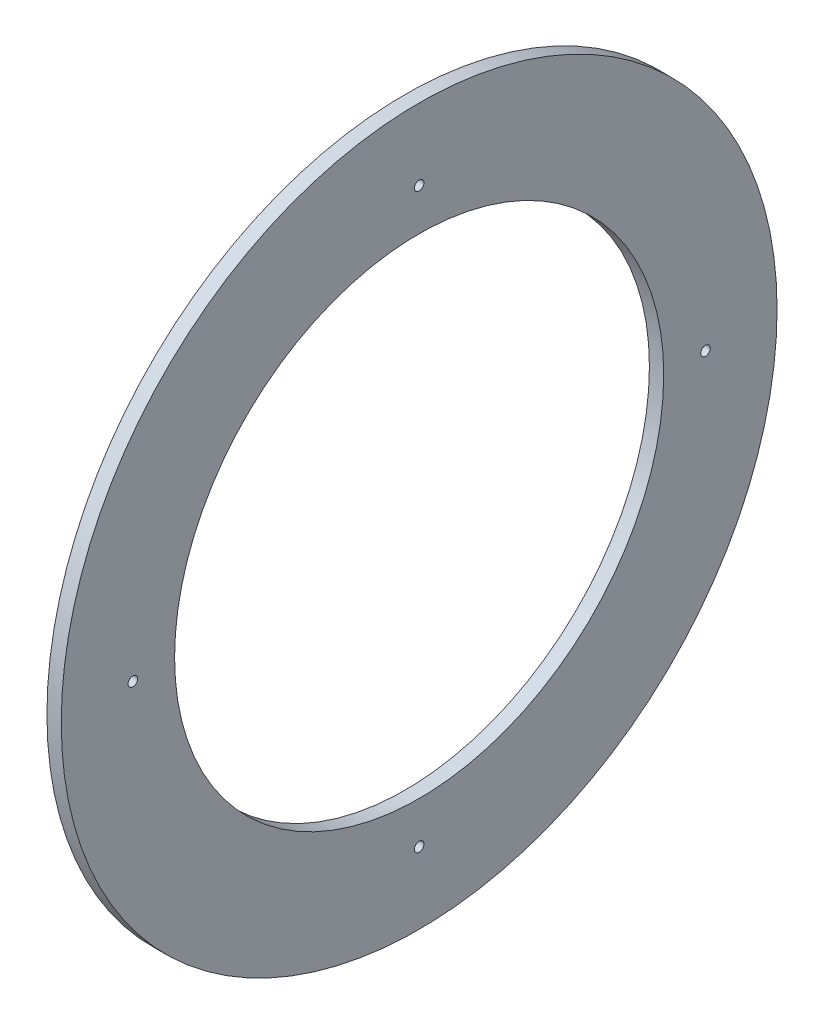
SolidWorks part; units mm, degrees
material "Balsa"
ref_plane "Plan de face" through (0, 0, 0) normal (0, 0, 1) x (1, 0, 0)
ref_plane "Plan de dessus" through (0, 0, 0) normal (0, 1, 0) x (1, 0, 0)
ref_plane "Plan de droite" through (0, 0, 0) normal (1, 0, 0) x (0, 0, -1)
sketch "Esquisse1" plane through (0, 0, 0) normal (1, 0, 0) x (0, 0, -1)
  circle A0 centre (0, 0) radius 51.25
  circle A1 centre (0, 0) radius 75
  dimension "D1" = 102.5
  dimension "D2" = 150
extrude "Boss.-Extru.1" add sketch "Esquisse1" along normal blind 3
sketch "Sketch1" plane through (3, 0, 0) normal (1, 0, 0) x (0, 0, -1)
  circle A0 centre (0, 60) radius 1
  circle A1 centre (60, 0) radius 1
  circle A2 centre (0, -60) radius 1
  circle A3 centre (-60, 0) radius 1
  point P11 (0, 0)
  dimension "D2" = 2
  dimension "D3" = 60
  dimension "D1" = 4
extrude "air vents" cut sketch "Sketch1" against normal through all
sketch "Sketch2" plane through (3, 0, 0) normal (1, 0, 0) x (0, 0, -1)
  line L0 (0, 0) -> (-48.0833, 48.0833) construction
  line L1 (-43.4871, 52.6795) -> (-81.6004, 90.7927)
  line L2 (-52.6795, 43.4871) -> (-92.274, 83.0816)
  line L3 (-92.274, 83.0816) -> (-81.6004, 90.7927)
  line L4 (0, 0) -> (0, 42.3711) construction
  arc A0 (-52.6795, 43.4871) -> (-43.4871, 52.6795) centre (-48.0833, 48.0833) ccw
  dimension "D1" = 13
  dimension "D2" = 68
  dimension "D3" = 45
extrude "Cut-Extrude1" [suppressed] cut sketch "Sketch2" against normal blind 10
equation "\"d_i_tube\"= 150mm'Inner Rocket Body Composite Tube Diameter"
equation "\"t_tube\"= 1.182mm'Thickness of Rocket Body Composite Tube"
equation "\"l_upper_body_tube\"= 949.3mm'Upper Rocket Body Composite Tube length"
equation "\"l_lower_body_tube\"= 816mm'Lower Rocket Body Composite Tube Length"
equation "\"d_a_NC\"= 154mm'Outer Diameter of Nosecone base"
equation "\"d_i_phenolic_tube\"= 152.3mm'Inner Phenolic Tube Diameter"
equation "\"t_phenolic_tube\"= 2mm'Thickness of Phenolic Body Tube"
equation "\"l_fin_cut\"= 220mm'Length of fin on Motor Retainer"
equation "\"t_SW-Panel\"= 11.482mm'Thickness of Sandwich-Panel"
equation "\"l_motor_tube\"=610mm'Length of phenolic motor tube"
equation "\"d_i_motor_tube\"=99.06mm'Inner diameter of phenolic motor tube"
equation "\"t_motor_tube\"=1.58mm'Thicknes of phenolic motor tube"
equation "\"D2@Esquisse1\"=\"d_i_tube\""
